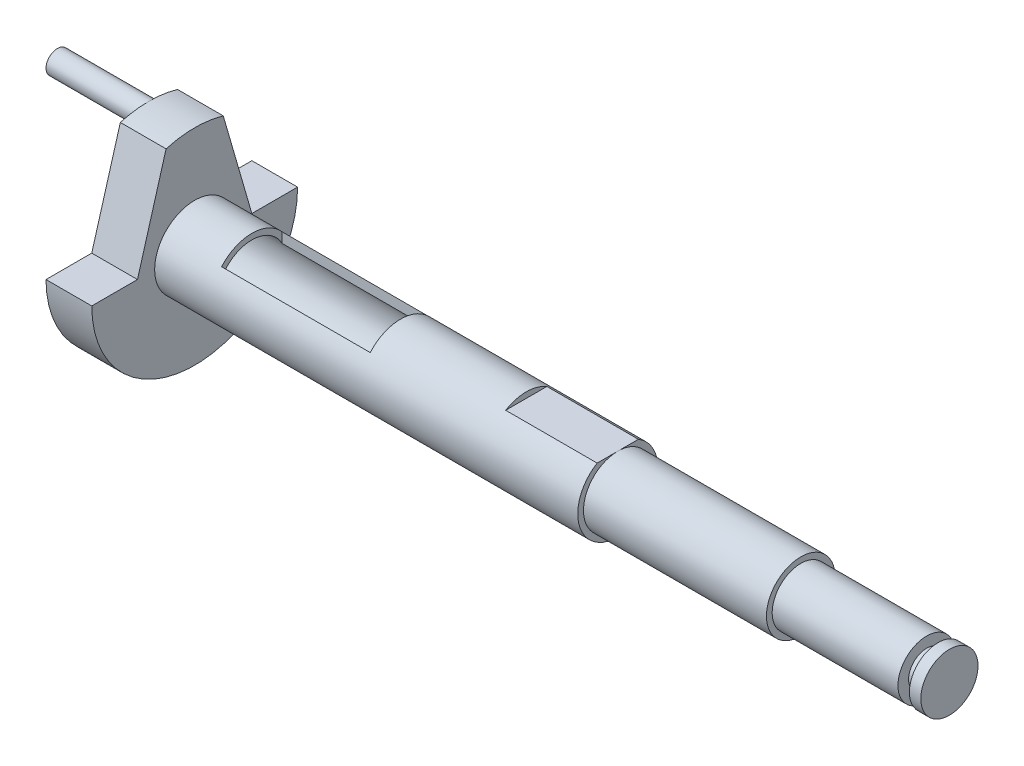
SolidWorks part; units mm, degrees
material "AISI 1045 Steel, cold drawn"
ref_plane "Front" through (0, 0, 0) normal (0, 0, 1) x (1, 0, 0)
ref_plane "Top" through (0, 0, 0) normal (0, 1, 0) x (1, 0, 0)
ref_plane "Right" through (0, 0, 0) normal (1, 0, 0) x (0, 0, -1)
sketch "Sketch1" plane through (0, 0, 0) normal (1, 0, 0) x (0, 0, -1)
  circle A0 centre (0, 0) radius 2.5
extrude "Boss-Extrude1" add sketch "Sketch1" along normal blind 1
sketch "Sketch2" plane through (0, 0, 0) normal (-1, 0, 0) x (0, 0, 1)
  circle A0 centre (0, 0) radius 1.57
extrude "Boss-Extrude2" add sketch "Sketch2" along normal blind 1
sketch "Sketch3" plane through (-1, 0, 0) normal (-1, 0, 0) x (0, 0, 1)
  circle A0 centre (0, 0) radius 2.5
extrude "Boss-Extrude3" add sketch "Sketch3" along normal blind 11
sketch "Sketch4" plane through (-12, 0, 0) normal (-1, 0, 0) x (0, 0, 1)
  circle A0 centre (0, 0) radius 3
extrude "Boss-Extrude4" add sketch "Sketch4" along normal blind 16
cosmetic thread "Cosmetic Thread3" parameters "D1"=11, "D2"=4.891
sketch "Sketch6" plane through (-28, 0, 0) normal (-1, 0, 0) x (0, 0, 1)
  circle A0 centre (0, 0) radius 3.5
  dimension "D1" = 7
extrude "Boss-Extrude6" add sketch "Sketch6" along normal blind 8
sketch "Sketch7" plane through (-28, 0, 0) normal (1, 0, 0) x (0, 0, -1)
  line L0 (-4.1005, 3) -> (3.9515, 3)
  line L1 (-4.1005, 3) -> (-4.1005, 4.2949)
  line L2 (-4.1005, 4.2949) -> (3.9515, 4.2949)
  line L3 (3.9515, 4.2949) -> (3.9515, 3)
  dimension "D1" = 3
extrude "Cut-Extrude1" cut sketch "Sketch7" against normal through all
sketch "Sketch8" plane through (-36, 0, 0) normal (-1, 0, 0) x (0, 0, 1)
  circle A0 centre (0, 0) radius 3.5
extrude "Boss-Extrude7" add sketch "Sketch8" along normal blind 29
sketch "Sketch9" plane through (-65, 0, 0) normal (-1, 0, 0) x (0, 0, 1)
  circle A0 centre (0, 0) radius 3
extrude "Cut-Extrude2" cut sketch "Sketch9" against normal blind 18
ref_plane "Plane1" through (0, 4, 0) normal (0, 1, 0) x (1, 0, 0)
sketch "Sketch10" plane through (0, 4, 0) normal (0, 1, 0) x (1, 0, 0)
  line L0 (-47, 2.6458) -> (-60, 2.6458)
  line L1 (-60, 2.6458) -> (-60, -2.6458)
  line L2 (-60, -2.6458) -> (-47, -2.6458)
  line L3 (-47, -2.6458) -> (-47, 2.6458)
  line L4 (-36, -1.8028) -> (-36, 1.8028) construction
  dimension "D1" = 11
  dimension "D2" = 13
extrude "Cut-Extrude3" cut sketch "Sketch10" against normal blind 3
sketch "Sketch11" plane through (-65, 0, 0) normal (-1, 0, 0) x (0, 0, 1)
  circle A0 centre (0, 0) radius 9
extrude "Boss-Extrude8" add sketch "Sketch11" along normal blind 4
sketch "Sketch12" plane through (-69, 0, 0) normal (-1, 0, 0) x (0, 0, 1)
  circle A0 centre (0, 0) radius 3
extrude "Cut-Extrude4" cut sketch "Sketch12" against normal blind 4
sketch "Sketch13" plane through (-69, 0, 0) normal (-1, 0, 0) x (0, 0, 1)
  line L0 (-9, 0) -> (-5, 0)
  line L1 (9, 0) -> (5, 0)
  line L2 (0, 0) -> (0, 9.2262) construction
  line L4 (-5, 0) -> (-2.5, 8.6458)
  line L5 (5, 0) -> (2.5, 8.6458)
  circle A0 centre (0, 0) radius 9 construction
  circle M7 centre (0, 0) radius 9
extrude "Cut-Extrude5" cut sketch "Sketch13" against normal blind 4 contours L0 L4 M7 | L5 L1 M7
sketch "Sketch14" plane through (-69, 0, 0) normal (-1, 0, 0) x (0, 0, 1)
  line L0 (0, 0) -> (0, 8) construction
  circle A0 centre (0, 8) radius 1
extrude "Boss-Extrude9" add sketch "Sketch14" along normal blind 8
